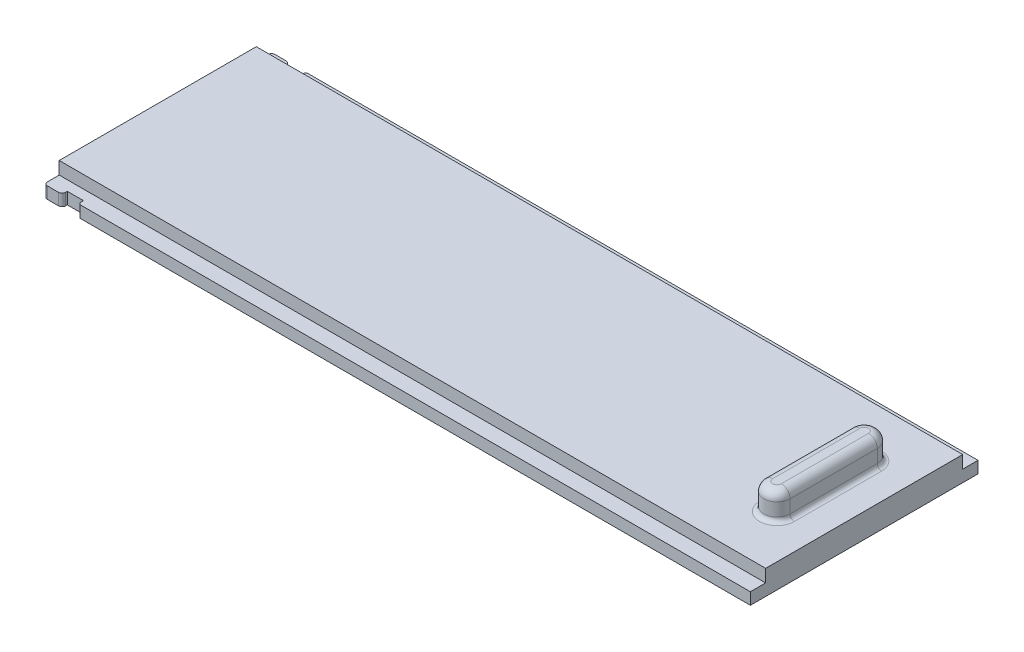
SolidWorks part; units mm, degrees
ref_plane "Front Plane" through (0, 0, 0) normal (0, 0, 1) x (1, 0, 0)
ref_plane "Top Plane" through (0, 0, 0) normal (0, 1, 0) x (1, 0, 0)
ref_plane "Right Plane" through (0, 0, 0) normal (1, 0, 0) x (0, 0, -1)
sketch "Sketch1" plane through (0, 0, 0) normal (0, 1, 0) x (1, 0, 0)
  line L1 (0, 0) -> (81, 0)
  line L2 (0, 0) -> (0, 29)
  line L3 (0, 29) -> (81, 29)
  line L4 (81, 0) -> (81, 29)
  dimension "D1" = 29
  dimension "D2" = 81
extrude "Boss-Extrude1" add sketch "Sketch1" along normal blind 3
sketch "Sketch2" plane through (81, 0, 0) normal (1, 0, 0) x (0, 0, -1)
  line L0 (0, 0) -> (29, 0) construction
  line L1 (0, 3) -> (3, 3)
  line L2 (0, 3) -> (0, 0)
  line L3 (0, 0) -> (1.25, 0)
  line L4 (3, 3) -> (3, 1.75)
  line L5 (3, 1.75) -> (1.25, 1.75)
  line L6 (1.25, 1.75) -> (1.25, 0)
  line L11 (14.5, 3) -> (14.5, 0) construction
  line L12 (0, 3) -> (29, 3) construction
  line L21 (29, 0) -> (27.75, 0)
  line L22 (29, 3) -> (26, 3)
  line L25 (27.75, 1.75) -> (26, 1.75)
  line L26 (26, 1.75) -> (26, 3)
  line L31 (27.75, 1.75) -> (27.75, 0)
  line L35 (29, 3) -> (29, 0)
  dimension "D1" = 1.25
  dimension "D2" = 1.25
  dimension "D3" = 3
extrude "Cut-Extrude2" cut sketch "Sketch2" against normal up to surface (81 mm away) up to face at (0, 1.5, -14.5)
sketch "Sketch4" plane through (81, 0, 0) normal (1, 0, 0) x (0, 0, -1)
  line L6 (27.75, 0) -> (27.55, 0)
  line L8 (27.75, 1.75) -> (27.75, 0)
  line L17 (14.5, 3) -> (14.5, 0) construction
  line L18 (3, 3) -> (26, 3) construction
  line L19 (1.25, 0) -> (27.75, 0) construction
  line L32 (25.8, 1.55) -> (25.8, 3)
  line L33 (27.55, 1.55) -> (25.8, 1.55)
  line L34 (27.55, 0) -> (27.55, 1.55)
  line L35 (26, 1.75) -> (27.75, 1.75)
  line L36 (26, 3) -> (26, 1.75)
  line L37 (25.8, 3) -> (26, 3)
  line L44 (3.2, 3) -> (3, 3)
  line L45 (3, 3) -> (3, 1.75)
  line L46 (3, 1.75) -> (1.25, 1.75)
  line L47 (1.45, 0) -> (1.45, 1.55)
  line L48 (1.45, 1.55) -> (3.2, 1.55)
  line L49 (3.2, 1.55) -> (3.2, 3)
  line L50 (1.45, 0) -> (1.45, 1.55)
  line L51 (1.45, 1.55) -> (3.2, 1.55)
  line L52 (3.2, 1.55) -> (3.2, 3)
  line L53 (1.25, 1.75) -> (1.25, 0)
  line L54 (1.25, 0) -> (1.45, 0)
  dimension "D1" = 0.2
extrude "Cut-Extrude3" cut sketch "Sketch4" against normal up to surface (81 mm away) up to face at (0, 1.625, -14.5)
sketch "Sketch6" plane through (0, 0, -1.45) normal (0, 0, 1) x (1, 0, 0)
  line L0 (0, 0.775) -> (3, 0.775) construction
  line L3 (2.075, 0) -> (3.925, 0)
  line L4 (2.075, 0) -> (2.075, 1.55)
  line L5 (2.075, 1.55) -> (3.925, 1.55)
  line L6 (3.925, 0) -> (3.925, 1.55)
  line L7 (2.075, 0) -> (3.925, 1.55) construction
  line L8 (2.075, 1.55) -> (3.925, 0) construction
  line L11 (0, 1.55) -> (81, 1.55) construction
  line L12 (0, 1.55) -> (0, 0) construction
  dimension "D1" = 3
  dimension "D3" = 1.85
  dimension "D4" = 0.775
extrude "Cut-Extrude5" cut sketch "Sketch6" against normal blind 0.6
fillet "Fillet6" radius 0.4 1 edges at (2.075, 0.775, -1.45)
chamfer "Chamfer2" distance 0.2 angle 45 1 edges at (3.925, 0.775, -1.45)
sketch "Sketch7" plane through (0, 0, -27.55) normal (0, 0, -1) x (-1, 0, 0)
  line L0 (-3, 0.775) -> (0, 0.775) construction
  line L3 (-2.075, 1.55) -> (-3.925, 1.55)
  line L4 (-2.075, 1.55) -> (-2.075, 0)
  line L5 (-2.075, 0) -> (-3.925, 0)
  line L6 (-3.925, 1.55) -> (-3.925, 0)
  line L7 (-2.075, 1.55) -> (-3.925, 0) construction
  line L8 (-2.075, 0) -> (-3.925, 1.55) construction
  line L9 (0, 1.55) -> (-81, 1.55) construction
  line L10 (0, 0) -> (0, 1.55) construction
  dimension "D1" = 3
  dimension "D3" = 1.85
  dimension "D4" = 0.775
extrude "Cut-Extrude6" cut sketch "Sketch7" against normal blind 0.6
fillet "Fillet7" radius 0.4 1 edges at (2.075, 0.775, -27.55)
chamfer "Chamfer3" distance 0.2 angle 45 1 edges at (3.925, 0.775, -27.55)
sketch "Sketch9" plane through (0, 3, 0) normal (0, 1, 0) x (1, 0, 0)
  line L0 (76, 9.5) -> (76, 19.5) construction
  line L1 (74.5, 9.5) -> (74.5, 19.5)
  line L2 (77.5, 9.5) -> (77.5, 19.5)
  line L3 (76, 8) -> (76, 3.2) construction
  line L5 (0, 3.2) -> (81, 3.2) construction
  line L14 (76, 21) -> (76, 25.8) construction
  line L15 (0, 25.8) -> (81, 25.8) construction
  line L16 (81, 3.2) -> (81, 25.8) construction
  arc A0 (74.5, 9.5) -> (77.5, 9.5) centre (76, 9.5) ccw
  arc A1 (77.5, 19.5) -> (74.5, 19.5) centre (76, 19.5) ccw
  point P2 (76, 14.5)
  dimension "D1" = 3
  dimension "D2" = 10
  dimension "D3" = 5
sketch "Sketch11" plane through (0, 0, 0) normal (0, -1, 0) x (-1, 0, 0)
  line L1 (0, 27.55) -> (-81, 27.55)
  line L2 (0, 27.55) -> (0, 1.45)
  line L3 (0, 1.45) -> (-81, 1.45)
  line L4 (-81, 27.55) -> (-81, 1.45)
extrude "Cut-Extrude7" cut sketch "Sketch11" against normal blind 0.2
fillet "Fillet8" radius 0.4 2 edges at (0, 0.875, -27.55) (0, 0.875, -1.45)
extrude "Boss-Extrude2" add sketch "Sketch9" along normal blind 3
fillet "Fillet9" radius 1 4 edges at (74.5, 6, -14.5) (76, 6, -21) (77.5, 6, -14.5) (76, 6, -8)
fillet "Fillet10" radius 0.5 4 edges at (74.5, 3, -14.5) (76, 3, -21) (77.5, 3, -14.5) (76, 3, -8)
